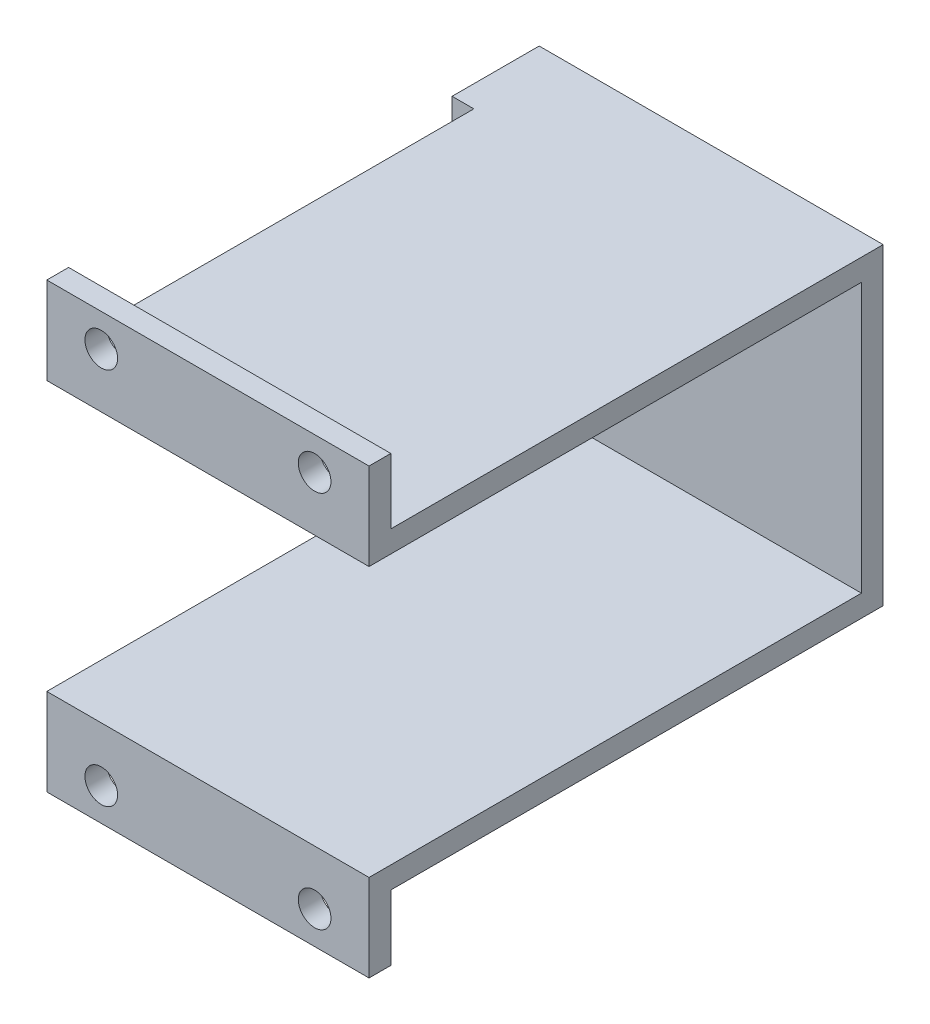
SolidWorks part; units mm, degrees
ref_plane "前视基准面" through (0, 0, 0) normal (0, 0, 1) x (1, 0, 0)
ref_plane "上视基准面" through (0, 0, 0) normal (0, 1, 0) x (1, 0, 0)
ref_plane "右视基准面" through (0, 0, 0) normal (1, 0, 0) x (0, 0, -1)
sketch "草图1" plane through (0, 0, 0) normal (0, 0, 1) x (1, 0, 0)
  line L1 (-14.8, -14.365) -> (14.8, -14.365)
  line L2 (-14.8, -14.365) -> (-14.8, 14.365)
  line L3 (-14.8, 14.365) -> (14.8, 14.365)
  line L4 (14.8, -14.365) -> (14.8, 14.365)
  line L5 (-14.8, -14.365) -> (14.8, 14.365) construction
  line L6 (-14.8, 14.365) -> (14.8, -14.365) construction
  point P0 (0, 0)
  dimension "D1" = 28.73
  dimension "D2" = 29.6
extrude "凸台-拉伸1" add sketch "草图1" along normal blind 47.23
sketch "草图2" plane through (0, 0, 47.23) normal (0, 0, 1) x (1, 0, 0)
  line L0 (-14.8, 14.365) -> (-14.8, -14.365) construction
  line L1 (14.8, -12.365) -> (-14.8, -12.365)
  line L2 (14.8, -12.365) -> (14.8, 12.365)
  line L3 (14.8, 12.365) -> (-14.8, 12.365)
  line L4 (-14.8, -12.365) -> (-14.8, 12.365)
  line L5 (14.8, -12.365) -> (-14.8, 12.365) construction
  line L6 (14.8, 12.365) -> (-14.8, -12.365) construction
  line L7 (14.8, 14.365) -> (-14.8, 14.365) construction
  point P0 (0, 0)
  dimension "D1" = 2
extrude "切除-拉伸1" cut sketch "草图2" against normal blind 45.23
sketch "草图3" plane through (-14.8, 0, 0) normal (-1, 0, 0) x (0, 0, 1)
  line L0 (47.23, -14.365) -> (0, -14.365) construction
  line L1 (0, 14.365) -> (8, 14.365)
  line L2 (0, 14.365) -> (0, -14.365)
  line L3 (0, -14.365) -> (8, -14.365)
  line L4 (8, 14.365) -> (8, -14.365)
  dimension "D1" = 8
extrude "凸台-拉伸2" add sketch "草图3" along normal blind 2
sketch "草图4" plane through (0, 0, 47.23) normal (0, 0, 1) x (1, 0, 0)
  line L1 (-14.8, 14.365) -> (14.8, 14.365)
  line L2 (-14.8, 14.365) -> (-14.8, 20.365)
  line L3 (-14.8, 20.365) -> (14.8, 20.365)
  line L4 (14.8, 14.365) -> (14.8, 20.365)
  dimension "D1" = 6
extrude "凸台-拉伸3" add sketch "草图4" against normal blind 2
sketch "草图5" plane through (0, 0, 45.23) normal (0, 0, -1) x (-1, 0, 0)
  line L0 (-14.8, 17.365) -> (14.8, 17.365) construction
  line L1 (-14.8, 14.365) -> (-14.8, 20.365) construction
  line L2 (14.8, 20.365) -> (14.8, 14.365) construction
  line L3 (-14.8, 20.365) -> (14.8, 20.365) construction
  line L4 (14.8, 14.365) -> (-14.8, 14.365) construction
  circle A0 centre (-9.8, 17.365) radius 1.5
  circle A1 centre (9.8, 17.365) radius 1.5
  dimension "D1" = 5
  dimension "D2" = 5
  dimension "D3" = 0
  dimension "D4" = 19.6
  dimension "D5" = 3
  dimension "D6" = 3
extrude "切除-拉伸2" cut sketch "草图5" against normal through all
mirror "镜向2" about plane through (0, 0, 0) normal (0, 1, 0) of "凸台-拉伸3", "切除-拉伸2"
